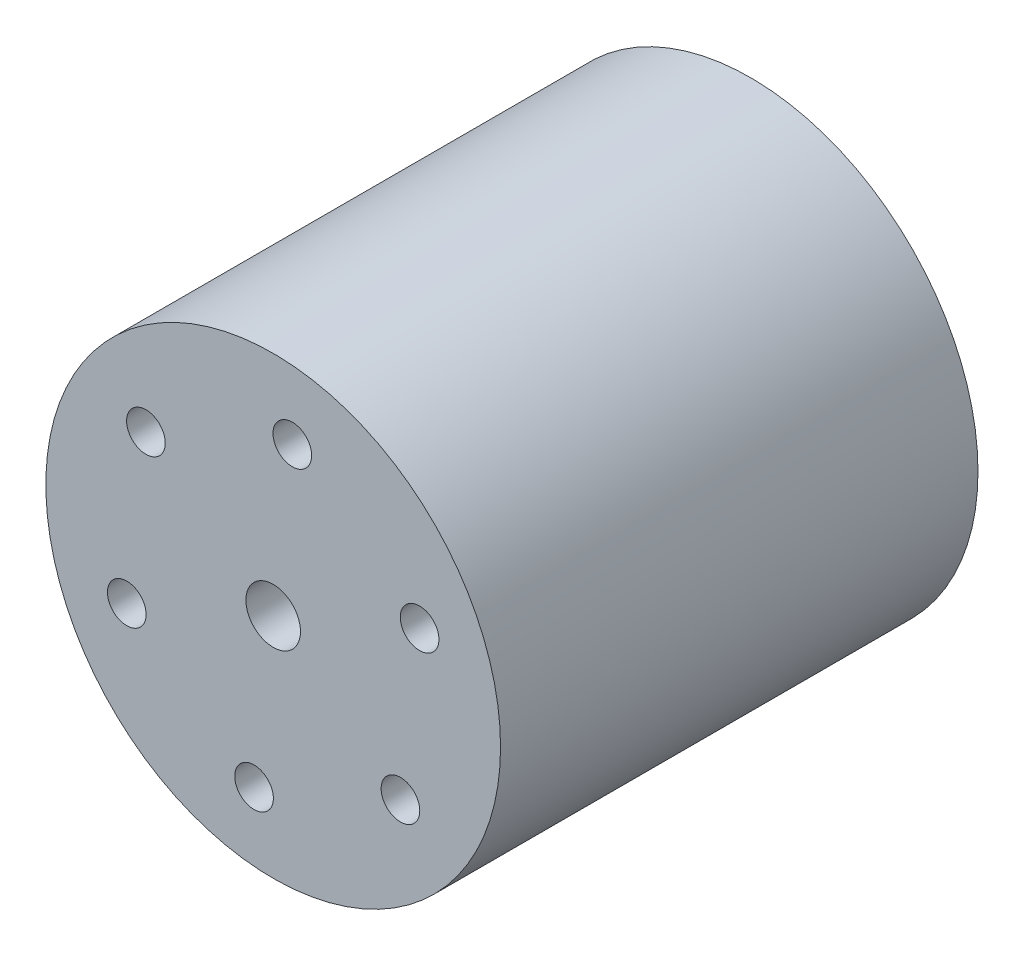
SolidWorks part; units mm, degrees
ref_plane "Front Plane" through (0, 0, 0) normal (0, 0, 1) x (1, 0, 0)
ref_plane "Top Plane" through (0, 0, 0) normal (0, 1, 0) x (1, 0, 0)
ref_plane "Right Plane" through (0, 0, 0) normal (1, 0, 0) x (0, 0, -1)
sketch "Sketch1" plane through (0, 0, 0) normal (0, 0, 1) x (1, 0, 0)
  line L1 (32.1957, 13.7272) -> (4.2097, 34.7459) construction
  line L2 (4.2097, 34.7459) -> (-27.986, 21.0187) construction
  line L3 (-27.986, 21.0187) -> (-32.1957, -13.7272) construction
  line L4 (-32.1957, -13.7272) -> (-4.2097, -34.7459) construction
  line L5 (-4.2097, -34.7459) -> (27.986, -21.0187) construction
  line L6 (27.986, -21.0187) -> (32.1957, 13.7272) construction
  circle A0 centre (0, 0) radius 50
  circle A1 centre (0, 0) radius 30.3109 construction
  circle A2 centre (-27.986, 21.0187) radius 4.25
  circle A3 centre (4.2097, 34.7459) radius 4.25
  circle A4 centre (32.1957, 13.7272) radius 4.25
  circle A5 centre (27.986, -21.0187) radius 4.25
  circle A6 centre (-4.2097, -34.7459) radius 4.25
  circle A7 centre (-32.1957, -13.7272) radius 4.25
  circle A8 centre (0, 0) radius 6
  dimension "D1" = 100
  dimension "D2" = 8.5
  dimension "D3" = 8.5
  dimension "D4" = 8.5
  dimension "D5" = 8.5
  dimension "D6" = 8.5
  dimension "D7" = 8.5
  dimension "D9" = 12
  dimension "D8" = 35
extrude "Boss-Extrude1" add sketch "Sketch1" along normal blind 105
sketch "Sketch2" plane through (0, 0, 0) normal (0, 0, -1) x (-1, 0, 0)
  circle A0 centre (0, 0) radius 6
extrude "Boss-Extrude2" add sketch "Sketch2" along normal blind 25.4 separate body
